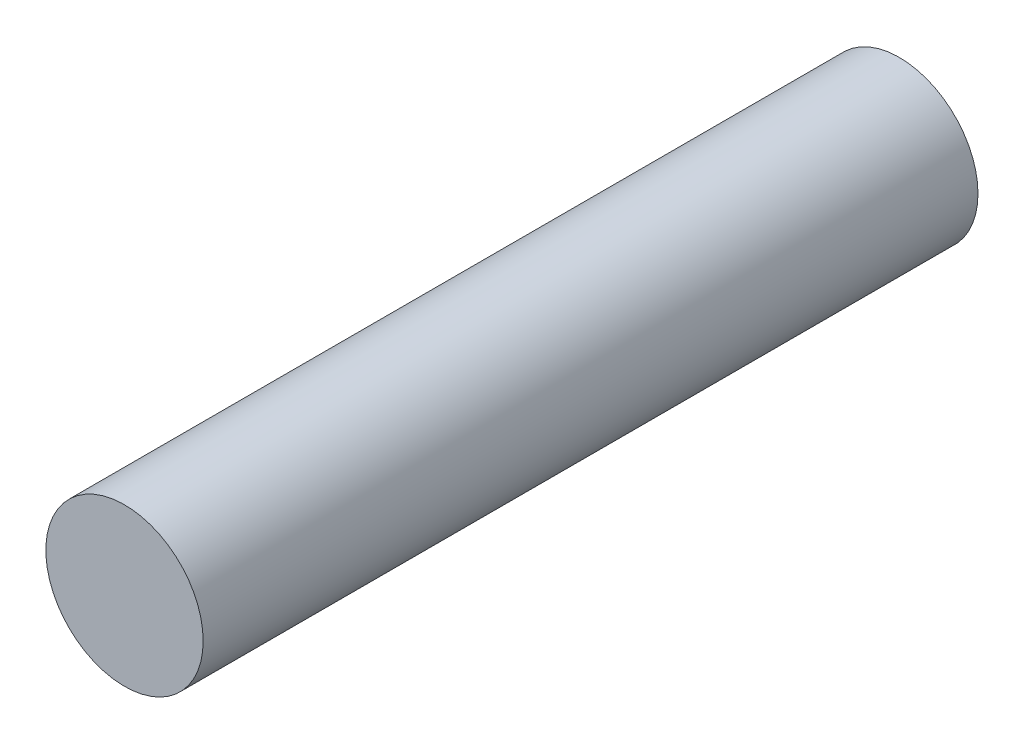
SolidWorks part; units mm, degrees
ref_plane "前视基准面" through (0, 0, 0) normal (0, 0, 1) x (1, 0, 0)
ref_plane "上视基准面" through (0, 0, 0) normal (0, 1, 0) x (1, 0, 0)
ref_plane "右视基准面" through (0, 0, 0) normal (1, 0, 0) x (0, 0, -1)
other "Configuration Table"
sketch "草图1" plane through (0, 0, 0) normal (0, 0, 1) x (1, 0, 0)
  circle A0 centre (0, 0) radius 1
extrude "凸台-拉伸2" add sketch "草图1" along normal blind 9.85
